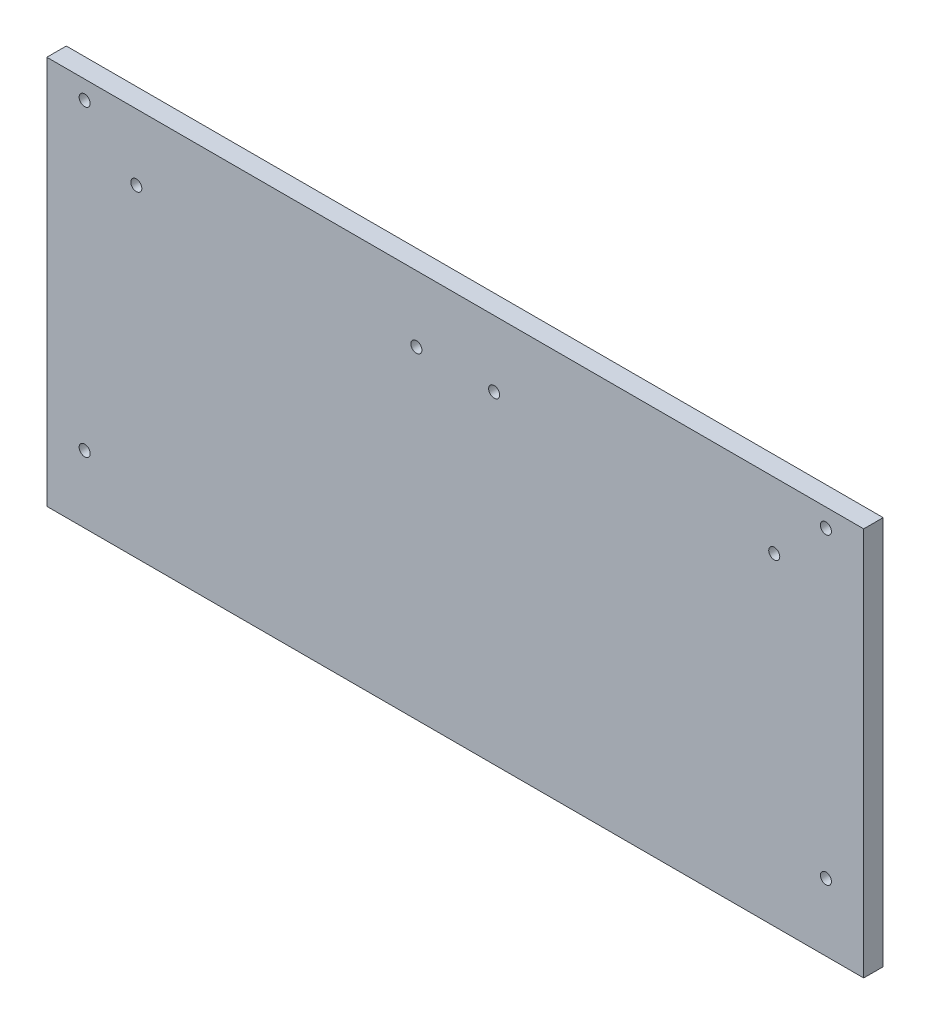
SolidWorks part; units mm, degrees
material "Acrylic (Medium-high impact)"
ref_plane "Front Plane" through (0, 0, 0) normal (0, 0, 1) x (1, 0, 0)
ref_plane "Top Plane" through (0, 0, 0) normal (0, 1, 0) x (1, 0, 0)
ref_plane "Right Plane" through (0, 0, 0) normal (1, 0, 0) x (0, 0, -1)
sketch "Sketch1" plane through (0, 0, 0) normal (0, 0, 1) x (1, 0, 0)
  line L1 (266.7, 127) -> (0, 127)
  line L2 (266.7, 127) -> (266.7, 0)
  line L3 (266.7, 0) -> (0, 0)
  line L4 (0, 127) -> (0, 0)
  line L5 (266.7, 127) -> (0, 0) construction
  line L6 (266.7, 0) -> (0, 127) construction
  point P0 (133.35, 63.5)
  dimension "D1" = 127
  dimension "D2" = 266.7
extrude "Boss-Extrude1" add sketch "Sketch1" along normal blind 6.35
hole_wizard "M3 Clearance Hole1" positions "Sketch2" profile "Sketch3" hole size "M3" standard "ANSI Metric" end condition through all
sketch "Sketch2" plane through (0, 0, 6.35) normal (0, 0, 1) x (1, 0, 0)
  line L0 (0, 127) -> (0, 0) construction
  line L1 (266.7, 127) -> (0, 127) construction
  line L2 (266.7, 0) -> (266.7, 127) construction
  line L3 (0, 0) -> (266.7, 0) construction
  point P0 (12.3444, 121.0056)
  point P2 (12.3444, 21.9964)
  point P4 (254.3556, 21.9964)
  point P6 (254.3556, 121.0056)
  dimension "D1" = 12.3444
  dimension "D2" = 5.9944
  dimension "D3" = 12.3444
  dimension "D4" = 21.9964
sketch "Sketch3" plane through (12.3444, 121.0056, 6.35) normal (1, 0, 0) x (0, -1, 0)
  line L0 (0, 0) -> (0, 6.35)
  line L1 (0, 6.35) -> (1.8, 6.35)
  line L2 (1.8, 6.35) -> (1.8, 0)
  line L5 (1.8, 0) -> (0, 0)
  line L11 (0, -6.35) -> (0, 107.95) construction
  dimension "Thru Hole Dia." = 3.6
  dimension "Thru Hole Depth" = 6.35
sketch "Sketch4" plane through (0, 0, 6.35) normal (0, 0, 1) x (1, 0, 0)
  line L0 (0, 127) -> (0, 0) construction
  line L1 (46.99, 107.95) -> (50.4952, 107.95)
  line L2 (46.99, 107.95) -> (46.99, 31.75)
  line L3 (46.99, 31.75) -> (50.4952, 31.75)
  line L4 (50.4952, 107.95) -> (50.4952, 31.75)
  line L5 (216.2048, 107.95) -> (219.71, 107.95)
  line L6 (216.2048, 107.95) -> (216.2048, 31.75)
  line L7 (216.2048, 31.75) -> (219.71, 31.75)
  line L8 (219.71, 107.95) -> (219.71, 31.75)
  line L9 (266.7, 0) -> (266.7, 127) construction
  line L10 (266.7, 127) -> (0, 127) construction
  dimension "D1" = 3.5052
  dimension "D2" = 76.2
  dimension "D3" = 46.99
  dimension "D4" = 46.99
  dimension "D5" = 19.05
extrude "Cut-Extrude1" [suppressed] cut sketch "Sketch4" against normal through all
sketch "Sketch5" plane through (0, 0, 6.35) normal (0, 0, 1) x (1, 0, 0)
  line L0 (0, 0) -> (266.7, 0)
  line L1 (266.7, 0) -> (266.7, 37.4822)
  line L2 (266.7, 0) -> (266.7, 127) construction
  line L3 (266.7, 37.4822) -> (0, 0)
  dimension "D1" = 8
extrude "Cut-Extrude2" [suppressed] cut sketch "Sketch5" against normal through all
sketch "Sketch6" plane through (0, 0, 6.35) normal (0, 0, 1) x (1, 0, 0)
  line L0 (25.4, 127) -> (27.94, 88.9)
  line L1 (266.7, 127) -> (0, 127) construction
  line L2 (27.94, 88.9) -> (30.48, 127)
  line L3 (30.48, 127) -> (25.4, 127)
  line L4 (0, 127) -> (0, 0) construction
  point P5 (27.94, 127)
  dimension "D1" = 38.1
  dimension "D2" = 5.08
  dimension "D3" = 25.4
extrude "Cut-Extrude3" [suppressed] cut sketch "Sketch6" against normal through all
pattern_linear "LPattern1" [suppressed] count 8 spacing 25.4
hole_wizard "M3 Clearance Hole2" positions "Sketch7" profile "Sketch8" hole size "M3" standard "ANSI Metric" end condition through all
sketch "Sketch7" plane through (0, 0, 6.35) normal (0, 0, 1) x (1, 0, 0)
  line L0 (0, 127) -> (0, 0) construction
  line L2 (266.7, 127) -> (0, 127) construction
  point P0 (29.21, 105.41)
  point P2 (120.65, 105.41)
  point P4 (146.05, 105.41)
  point P6 (237.49, 105.41)
  dimension "D1" = 91.44
  dimension "D2" = 91.44
  dimension "D3" = 25.4
  dimension "D4" = 29.21
  dimension "D5" = 21.59
sketch "Sketch8" plane through (29.21, 105.41, 6.35) normal (1, 0, 0) x (0, -1, 0)
  line L0 (0, 0) -> (0, 6.35)
  line L1 (0, 6.35) -> (1.8, 6.35)
  line L2 (1.8, 6.35) -> (1.8, 0)
  line L5 (1.8, 0) -> (0, 0)
  line L11 (0, -6.35) -> (0, 107.95) construction
  dimension "Thru Hole Dia." = 3.6
  dimension "Thru Hole Depth" = 6.35
sketch "Sketch9" [suppressed] plane through (0, 0, 6.35) normal (0, 0, 1) x (1, 0, 0)
  line L0 (0, 0) -> (266.7, 0) construction
  line L1 (49.53, 105.918) -> (217.17, 105.918)
  line L2 (49.53, 105.918) -> (49.53, 20.828)
  line L3 (49.53, 20.828) -> (217.17, 20.828)
  line L4 (217.17, 105.918) -> (217.17, 20.828)
  line L5 (49.53, 105.918) -> (217.17, 20.828) construction
  line L6 (49.53, 20.828) -> (217.17, 105.918) construction
  point P0 (133.35, 63.373)
  point P8 (133.35, 0)
  dimension "D1" = 167.64
  dimension "D2" = 85.09
  dimension "D3" = 20.828
extrude "Cut-Extrude4" [suppressed] cut sketch "Sketch9" against normal through all
hole_wizard "#10 Clearance Hole1" [suppressed] positions "Sketch10" profile "Sketch11" hole size "#10" standard "ANSI Inch"
sketch "Sketch10" plane through (0, 0, 6.35) normal (0, 0, 1) x (1, 0, 0)
  line L0 (49.53, 20.828) -> (217.17, 20.828) construction
  line L1 (107.95, 10.5156) -> (158.75, 10.5156) construction
  line L2 (133.35, 20.828) -> (133.35, 10.5156) construction
  line L3 (49.53, 20.828) -> (217.17, 20.828) construction
  line L4 (71.4375, 10.5156) -> (107.95, 10.5156) construction
  line L7 (158.75, 10.5156) -> (195.2625, 10.5156) construction
  point P0 (71.4375, 10.5156)
  point P2 (107.95, 10.5156)
  point P4 (158.75, 10.5156)
  point P6 (195.2625, 10.5156)
  point P25 (89.6937, 10.5156)
  point P27 (177.0062, 10.5156)
  dimension "D1" = 36.5125
  dimension "D3" = 50.8
  dimension "D4" = 10.3124
sketch "Sketch11" plane through (71.4375, 10.5156, 6.35) normal (1, 0, 0) x (0, -1, 0)
  line L0 (0, 0) -> (0, 6.35)
  line L1 (0, 6.35) -> (2.8067, 6.35)
  line L2 (2.8067, 6.35) -> (2.8067, 0)
  line L5 (2.8067, 0) -> (0, 0)
  line L11 (0, -6.35) -> (0, 107.95) construction
  dimension "Thru Hole Dia." = 5.6134
  dimension "Thru Hole Depth" = 6.35
fillet "Fillet1" [suppressed] radius 6.35
